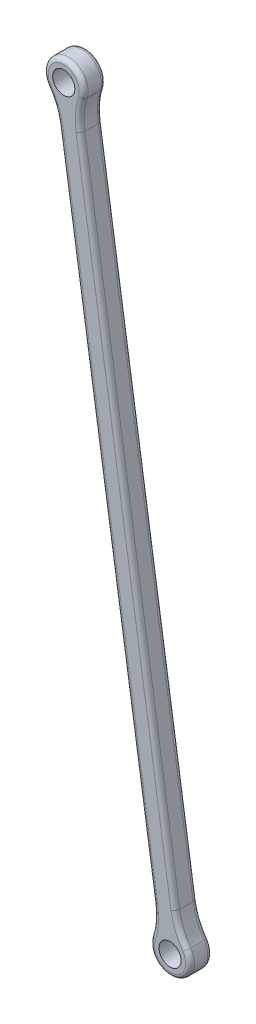
SolidWorks part; units mm, degrees
ref_plane "Front Plane" through (0, 0, 0) normal (0, 0, 1) x (1, 0, 0)
ref_plane "Top Plane" through (0, 0, 0) normal (0, 1, 0) x (1, 0, 0)
ref_plane "Right Plane" through (0, 0, 0) normal (1, 0, 0) x (0, 0, -1)
sketch "Sketch1" plane through (0, 0, 0) normal (0, 0, 1) x (1, 0, 0)
  line L0 (0, 0) -> (0, 28420.5788) construction
  line L1 (0, 0) -> (-28420.5788, 0) construction
  line L2 (-23, 10) -> (-28, 10)
  line L3 (-23, 0) -> (23, 0)
  line L4 (-23, 0) -> (-23, 10)
  line L5 (-23, 10) -> (23, 10)
  line L6 (23, 0) -> (23, 10)
  line L7 (-28, 10) -> (-41.8608, 50.4677)
  line L8 (-24.6313, 80.3256) -> (15.2446, 88.1625)
  line L9 (23, 10) -> (28, 10)
  line L10 (28, 10) -> (39.4051, 19.57)
  line L11 (39.4051, 19.57) -> (39.4051, 38.57)
  line L12 (39.4051, 38.57) -> (22.9346, 83.8223)
  line L13 (-20.22, 57.88) -> (-41.0516, 204.4066) construction
  line L14 (16.5541, 81.5) -> (-4.2776, 228.0266) construction
  line L15 (-75.8246, 230.8844) -> (-41.0516, 204.4066) construction
  line L16 (-41.0516, 204.4066) -> (-4.2776, 228.0266) construction
  line L17 (-4.2776, 228.0266) -> (-75.8246, 230.8844) construction
  line L18 (-75.8246, 230.8844) -> (-226.1828, 176.1814) construction
  line L19 (-204.7956, 140.0346) -> (9.2044, 224.1635) construction
  line L20 (-226.1828, 176.1814) -> (-204.7956, 140.0346) construction
  line L21 (-204.7956, 140.0346) -> (-256.0612, 159.9555) construction
  line L22 (-256.0612, 159.9555) -> (-226.1828, 176.1814) construction
  line L23 (-20.22, 57.88) -> (33.1708, 65.9687)
  line L24 (33.1708, 65.9687) -> (9.2044, 224.1635)
  circle A0 centre (-20.22, 57.88) radius 22.875 construction
  circle A1 centre (16.5541, 81.5) radius 6.79 construction
  arc A2 (-41.8608, 50.4677) -> (-24.6313, 80.3256) centre (-20.22, 57.88) cw
  arc A3 (15.2446, 88.1625) -> (22.9346, 83.8223) centre (16.5541, 81.5) cw
  circle A4 centre (-20.22, 57.88) radius 17.5 construction
  circle A5 centre (16.5541, 81.5) radius 7.5 construction
  circle A6 centre (-41.0516, 204.4066) radius 13.1881 construction
  circle A7 centre (-4.2776, 228.0266) radius 8.7345 construction
  circle A8 centre (-75.8246, 230.8844) radius 8.7345 construction
  circle A9 centre (-226.1828, 176.1814) radius 8.1525 construction
  circle A10 centre (-204.7956, 140.0346) radius 9.1166 construction
  dimension "D7" = 45.75
  dimension "D8" = 13.58
  dimension "D14" = 35
  dimension "D15" = 15
  dimension "D1" = 46
  dimension "D2" = 10
  dimension "D3" = 57.88
  dimension "D4" = 20.22
  dimension "D5" = 16.5541
  dimension "D6" = 81.5
  dimension "D9" = 5
  dimension "D10" = 5
  dimension "D11" = 140
  dimension "D12" = 19
  dimension "D13" = 160
  dimension "D16" = 148
  dimension "D17" = 110
  dimension "D18" = 160
  dimension "D19" = 54
  dimension "D20" = 214
  dimension "D21" = 42
  dimension "D22" = 34
  dimension "D23" = 55
  dimension "D24" = 54
  dimension "D25" = 160
sketch "Sketch3" plane through (0, 0, 0) normal (0, 0, 1) x (1, 0, 0)
  line L0 (33.1708, 65.9687) -> (9.2044, 224.1635) construction
  line L1 (33.1708, 65.9687) -> (9.2044, 224.1635)
  line L2 (9.2044, 224.1635) -> (33.1708, 65.9687) construction
  line L3 (11.6762, 224.538) -> (35.6426, 66.3431)
  line L4 (6.7326, 223.789) -> (30.699, 65.5942)
  arc A0 (12.2366, 220.8385) -> (7.293, 220.0896) centre (9.2044, 224.1635) ccw
  arc A1 (30.1385, 69.2936) -> (35.0821, 70.0426) centre (33.1708, 65.9687) ccw
  arc A2 (11.6762, 224.538) -> (6.7326, 223.789) centre (9.2044, 224.1635) ccw
  arc A3 (30.699, 65.5942) -> (35.6426, 66.3431) centre (33.1708, 65.9687) ccw
  circle A4 centre (9.2044, 224.1635) radius 2.5
  circle A5 centre (33.1708, 65.9687) radius 2.5
  point P4 (21.1876, 145.0661)
  dimension "D1" = 9
  dimension "D2" = 9
  dimension "D3" = 5
extrude "Boss-Extrude2" add sketch "Sketch3" along normal mid plane 5 contours A5 L1 A4 L4 | A5 L3 A4 L1 | A3 L4 A1 L3 | A2 L3 A0 L4
fillet "Fillet4" radius 15 4 edges at (30.1385, 69.2936, 0) (35.0821, 70.0426, 0) (12.2366, 220.8385, 0) (7.293, 220.0896, 0)
fillet "Fillet3" radius 1 16 edges at (18.7158, 144.6916, -2.5) (18.7158, 144.6916, 2.5) (8.5303, 228.6127, 2.5) (8.5303, 228.6127, -2.5) (23.6594, 145.4406, 2.5) (23.6594, 145.4406, -2.5) (33.8448, 61.5194, 2.5) (33.8448, 61.5194, -2.5) (29.534, 70.6826, 2.5) (29.534, 70.6826, -2.5) (7.127, 218.5839, 2.5) (7.127, 218.5839, -2.5) (12.8412, 219.4496, 2.5) (12.8412, 219.4496, -2.5) (35.2481, 71.5483, 2.5) (35.2481, 71.5483, -2.5)
sketch "Sketch2" plane through (0, 0, 0) normal (0, 0, 1) x (1, 0, 0)
  line L0 (16.5541, 81.5) -> (-4.2776, 228.0266) construction
  line L1 (15.9207, 85.9552) -> (-3.6442, 223.5714)
  line L2 (-4.2776, 228.0266) -> (16.5541, 81.5) construction
  line L3 (1.2747, 220.9434) -> (19.9122, 89.85)
  line L4 (-7.6357, 219.6766) -> (11.0018, 88.5832)
  arc A0 (1.2747, 220.9434) -> (-7.6357, 219.6766) centre (-4.2776, 228.0266) ccw
  arc A1 (11.0018, 88.5832) -> (19.9122, 89.85) centre (16.5541, 81.5) ccw
  arc A2 (0.1776, 228.66) -> (-8.7328, 227.3932) centre (-4.2776, 228.0266) ccw
  arc A3 (12.0989, 80.8666) -> (21.0093, 82.1334) centre (16.5541, 81.5) ccw
  circle A4 centre (-4.2776, 228.0266) radius 4.5
  circle A5 centre (16.5541, 81.5) radius 4.5
  point P4 (6.1383, 154.7633)
  dimension "D1" = 18
  dimension "D2" = 18
  dimension "D3" = 9
